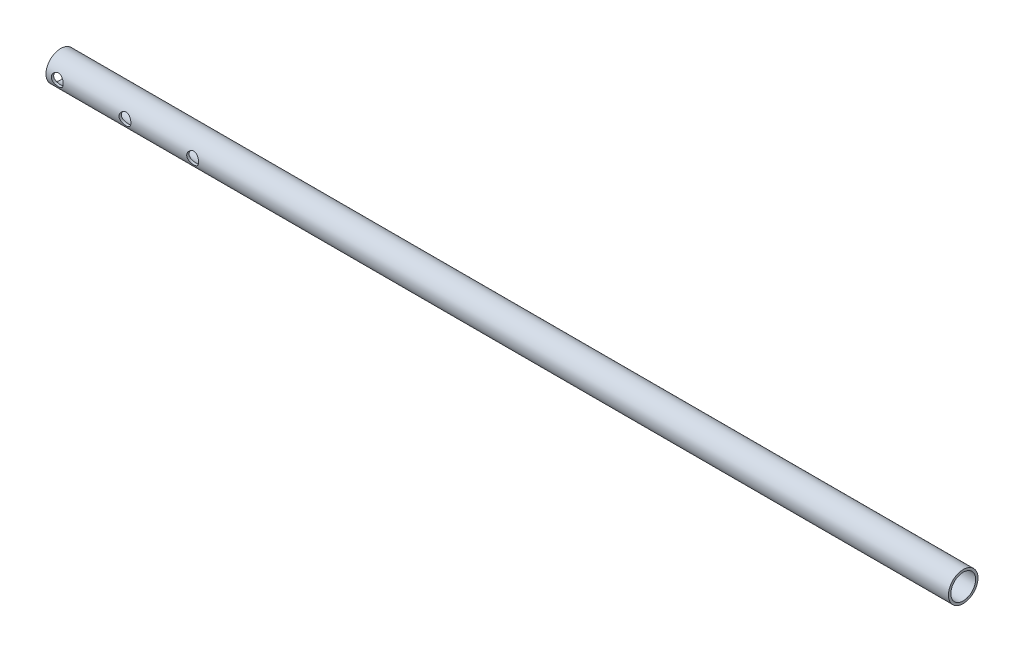
SolidWorks part; units mm, degrees
material "Thornel VCB-20 Carbon Cloth"
ref_plane "Front Plane" through (0, 0, 0) normal (0, 0, 1) x (1, 0, 0)
ref_plane "Top Plane" through (0, 0, 0) normal (0, 1, 0) x (1, 0, 0)
ref_plane "Right Plane" through (0, 0, 0) normal (1, 0, 0) x (0, 0, -1)
sketch "Sketch1" plane through (0, 0, 0) normal (1, 0, 0) x (0, 0, -1)
  circle A0 centre (0, 0) radius 5.5
  circle A1 centre (0, 0) radius 6.55
  dimension "D1" = 13.1
  dimension "D2" = 11
extrude "Boss-Extrude1" add sketch "Sketch1" along normal blind 400
sketch "Sketch2" plane through (0, 0, 0) normal (0, 0, 1) x (1, 0, 0)
  line L0 (0, 0) -> (400, 0) construction
  line L1 (0, 6.55) -> (0, -6.55) construction
  line L2 (400, -6.55) -> (400, 6.55) construction
  line L3 (5, 0) -> (35, 0) construction
  circle A0 centre (5, 0) radius 2.625
  circle A1 centre (35, 0) radius 2.625
  circle A2 centre (65, 0) radius 2.625
  dimension "D2" = 5.25
  dimension "D1" = 5
  dimension "D4" = 30
  dimension "D3" = 3
extrude "Cut-Extrude1" cut sketch "Sketch2" against normal through all both and the other way through all
